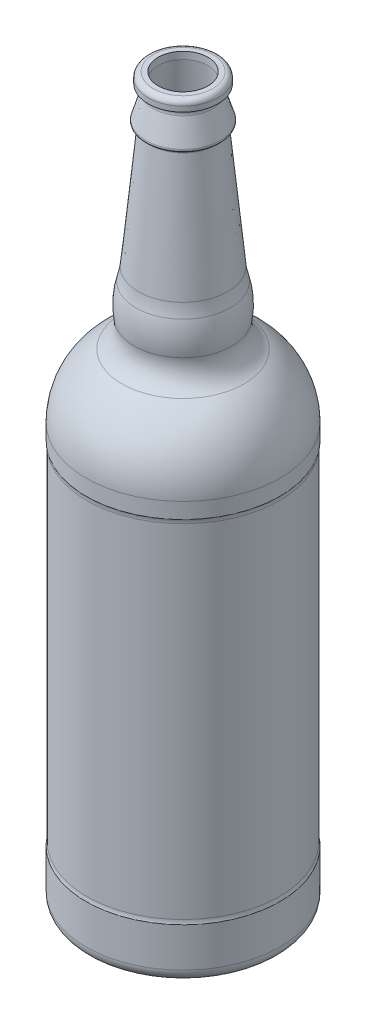
SolidWorks part; units mm, degrees
ref_plane "Front Plane" through (0, 0, 0) normal (0, 0, 1) x (1, 0, 0)
ref_plane "Top Plane" through (0, 0, 0) normal (0, 1, 0) x (1, 0, 0)
ref_plane "Right Plane" through (0, 0, 0) normal (1, 0, 0) x (0, 0, -1)
sketch "Sketch1" plane through (0, 0, 0) normal (0, 0, 1) x (1, 0, 0)
  line L0 (0, 0) -> (0, 251.2246) construction
  line L1 (0, 3.175) -> (-46.8413, 3.175) construction
  line L2 (37, 5) -> (37, 20)
  line L3 (0, 0) -> (40.8953, 0) construction
  line L4 (36.75, 21.5612) -> (36.75, 152.4388)
  line L5 (11.335, 276) -> (9.5, 276)
  line L6 (9.5, 276) -> (9.5, 273.2607)
  line L7 (37, 160) -> (37, 154)
  line L8 (13.335, 274) -> (13.335, 272)
  line L9 (11.4206, 269.4213) -> (14.1812, 260.2894)
  line L10 (12.5047, 257.922) -> (17.0171, 211.7059)
  line L11 (35.5, 5) -> (35.5, 19.7759)
  line L12 (35.25, 21.5612) -> (35.25, 152.4388)
  line L13 (35.5, 160) -> (35.5, 154.2241)
  line L14 (9.5, 273.2607) -> (15.5242, 211.5601)
  line L15 (11.0118, 257.7762) -> (15.5242, 211.5601) construction
  line L16 (0, 4.675) -> (0, 3.175)
  arc A0 (0, 3.175) -> (31.0175, 0.0975) centre (0, -154.6723) cw
  arc A1 (31.0175, 0.0975) -> (37, 5) centre (32, 5) ccw
  arc A2 (37, 20) -> (36.75, 21.5612) centre (41.75, 21.5612) cw
  arc A3 (36.75, 152.4388) -> (37, 154) centre (41.75, 152.4388) cw
  arc A4 (37, 160) -> (23.3052, 184.3527) centre (8.5, 160) ccw
  arc A5 (11.335, 276) -> (13.335, 274) centre (11.335, 274) cw
  arc A6 (13.335, 272) -> (11.4206, 269.4213) centre (13.335, 270) ccw
  arc A7 (14.1812, 260.2894) -> (13.362, 259.0096) centre (13.224, 260) cw
  arc A8 (13.362, 259.0096) -> (12.5047, 257.922) centre (13.5, 258.0191) ccw
  arc A9 (23.3052, 184.3527) -> (18.6299, 194.504) centre (28.5, 192.8976) cw
  arc A10 (18.6299, 194.504) -> (17.9411, 206.7788) centre (-9.5, 199.0822) ccw
  arc A11 (17.9411, 206.7788) -> (17.0171, 211.7059) centre (45.3822, 214.4753) cw
  arc A12 (0, 4.675) -> (31.3122, 1.5682) centre (0, -154.6723) cw
  arc A13 (31.3122, 1.5682) -> (35.5, 5) centre (32, 5) ccw
  arc A14 (35.5, 19.7759) -> (35.25, 21.5612) centre (41.75, 21.5612) cw
  arc A15 (35.25, 152.4388) -> (35.5, 154.2241) centre (41.75, 152.4388) cw
  arc A16 (35.5, 160) -> (22.526, 183.071) centre (8.5, 160) ccw
  arc A17 (22.526, 183.071) -> (17.1494, 194.7449) centre (28.5, 192.8976) cw
  arc A18 (17.1494, 194.7449) -> (16.4968, 206.3737) centre (-9.5, 199.0822) ccw
  arc A19 (16.4968, 206.3737) -> (15.5242, 211.5601) centre (45.3822, 214.4753) cw
  dimension "D3" = 5
  dimension "D7" = 5
  dimension "D11" = 28.5
  dimension "D12" = 2
  dimension "D14" = 28.448
  dimension "D17" = 1
  dimension "D18" = 37
  dimension "D19" = 38
  dimension "D20" = 10
  dimension "D21" = 25
  dimension "D1" = 74
  dimension "D2" = 3.175
  dimension "D4" = 276
  dimension "D5" = 19
  dimension "D6" = 73.5
  dimension "D8" = 20
  dimension "D9" = 154
  dimension "D10" = 160
  dimension "D13" = 26.67
  dimension "D15" = 16
  dimension "D16" = 4
  dimension "D22" = 1.5
revolve "Revolve1" add sketch "Sketch1" angle 360 about L0
